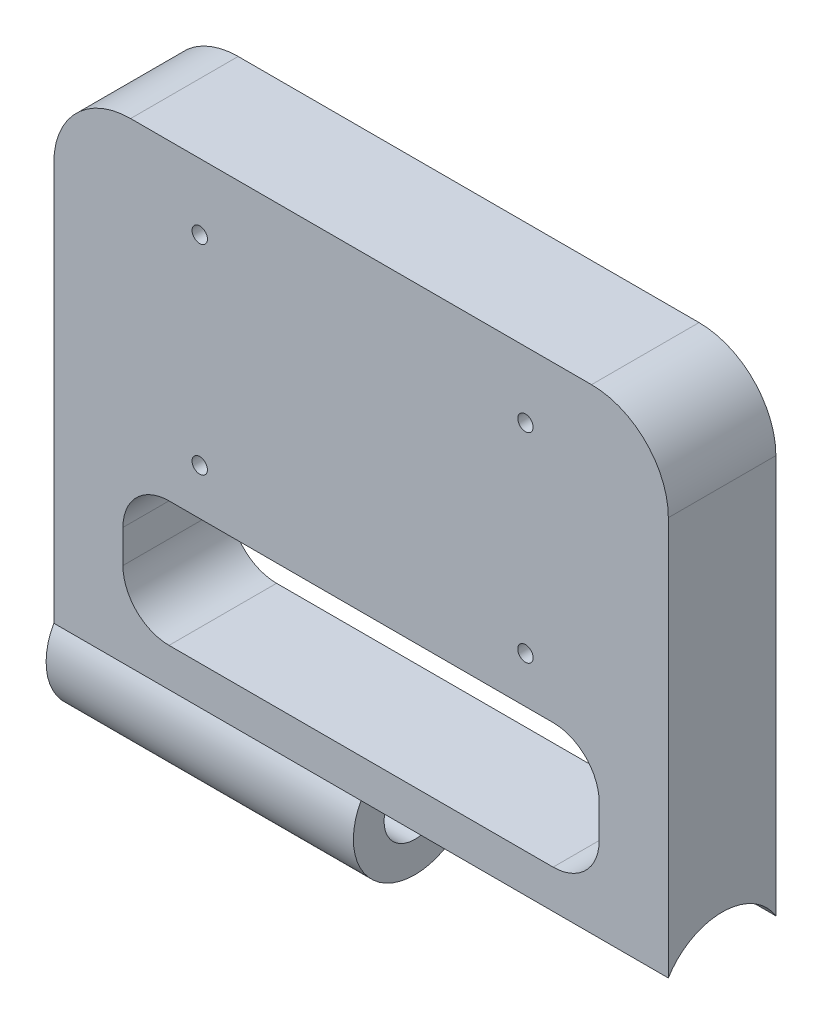
SolidWorks part; units mm, degrees
material "PLA"
ref_plane "Front Plane" through (0, 0, 0) normal (0, 0, 1) x (1, 0, 0)
ref_plane "Top Plane" through (0, 0, 0) normal (0, 1, 0) x (1, 0, 0)
ref_plane "Right Plane" through (0, 0, 0) normal (1, 0, 0) x (0, 0, -1)
sketch "Sketch1" plane through (0, 0, 0) normal (0, 0, 1) x (1, 0, 0)
  line L1 (-22.2292, -0.4536) -> (17.7708, -0.4536)
  line L2 (-22.2292, -0.4536) -> (-22.2292, -33.5356)
  line L3 (-22.2292, -33.5356) -> (17.7708, -33.5356)
  line L4 (17.7708, -0.4536) -> (17.7708, -33.5356)
  dimension "D1" = 40
  dimension "D2" = 33.082
extrude "Boss-Extrude1" add sketch "Sketch1" along normal blind 7
sketch "Sketch2" plane through (17.7708, 0, 0) normal (1, 0, 0) x (0, 0, -1)
  line L0 (-7, -33.5356) -> (0, -33.5356) construction
  circle A0 centre (-3.5, -33.5356) radius 4.1
  dimension "D1" = 8.2
extrude "Cut-Extrude1" cut sketch "Sketch2" against normal blind 20
ref_plane "Plane1" through (-13.2292, 0, 0) normal (1, 0, 0) x (0, 0, -1)
sketch "Sketch3" plane through (-13.2292, 0, 0) normal (1, 0, 0) x (0, 0, -1)
  circle A0 centre (-3.5, -33.3367) radius 4
  circle A1 centre (-3.5, -33.3367) radius 2
  dimension "D1" = 8
  dimension "D2" = 4
extrude "Boss-Extrude2" add sketch "Sketch3" against normal blind 9 and the other way blind 11
fillet "Fillet1" radius 5 2 edges at (-22.2292, -0.4536, 3.5) (17.7708, -0.4536, 3.5)
sketch "Sketch4" plane through (0, 0, 0) normal (0, 0, -1) x (-1, 0, 0)
  line L0 (22.2292, -5.4536) -> (22.2292, -31.4002) construction
  line L1 (17.7292, -20.7536) -> (-13.2708, -20.7536)
  line L2 (17.7292, -20.7536) -> (17.7292, -28.9002)
  line L3 (17.7292, -28.9002) -> (-13.2708, -28.9002)
  line L4 (-13.2708, -20.7536) -> (-13.2708, -28.9002)
  line L5 (22.2292, -5.4536) -> (22.2292, -31.4002) construction
  line L6 (22.2292, -31.4002) -> (2.2292, -31.4002) construction
  line L8 (-12.7708, -0.4536) -> (17.2292, -0.4536) construction
  circle A0 centre (-8.4708, -4.7536) radius 0.5
  circle A1 centre (12.7292, -4.7536) radius 0.5
  circle A2 centre (12.7292, -17.7536) radius 0.5
  circle A3 centre (-8.4708, -17.7536) radius 0.5
  dimension "D1" = 1
  dimension "D2" = 1
  dimension "D3" = 1
  dimension "D4" = 1
  dimension "D9" = 9.5
  dimension "D10" = 21.2
  dimension "D11" = 13
  dimension "D12" = 13
  dimension "D13" = 21.2
  dimension "D14" = 9.5
  dimension "D15" = 4.3
  dimension "D16" = 4.3
  dimension "D8" = 3
  dimension "D5" = 31
  dimension "D6" = 4.5
  dimension "D7" = 2.5
extrude "Cut-Extrude2" cut sketch "Sketch4" against normal through all
fillet "Fillet2" radius 3 4 edges at (13.2708, -20.7536, 3.5) (13.2708, -28.9002, 3.5) (-17.7292, -28.9002, 3.5) (-17.7292, -20.7536, 3.5)
sketch "Sketch5" plane through (-22.2292, 0, 0) normal (-1, 0, 0) x (0, 0, 1)
  circle A0 centre (3.5, -33.3367) radius 2
  arc A1 (1.5099, -33.5356) -> (5.4901, -33.5356) centre (3.5, -33.3367) ccw construction
extrude "Cut-Extrude3" cut sketch "Sketch5" against normal through all
